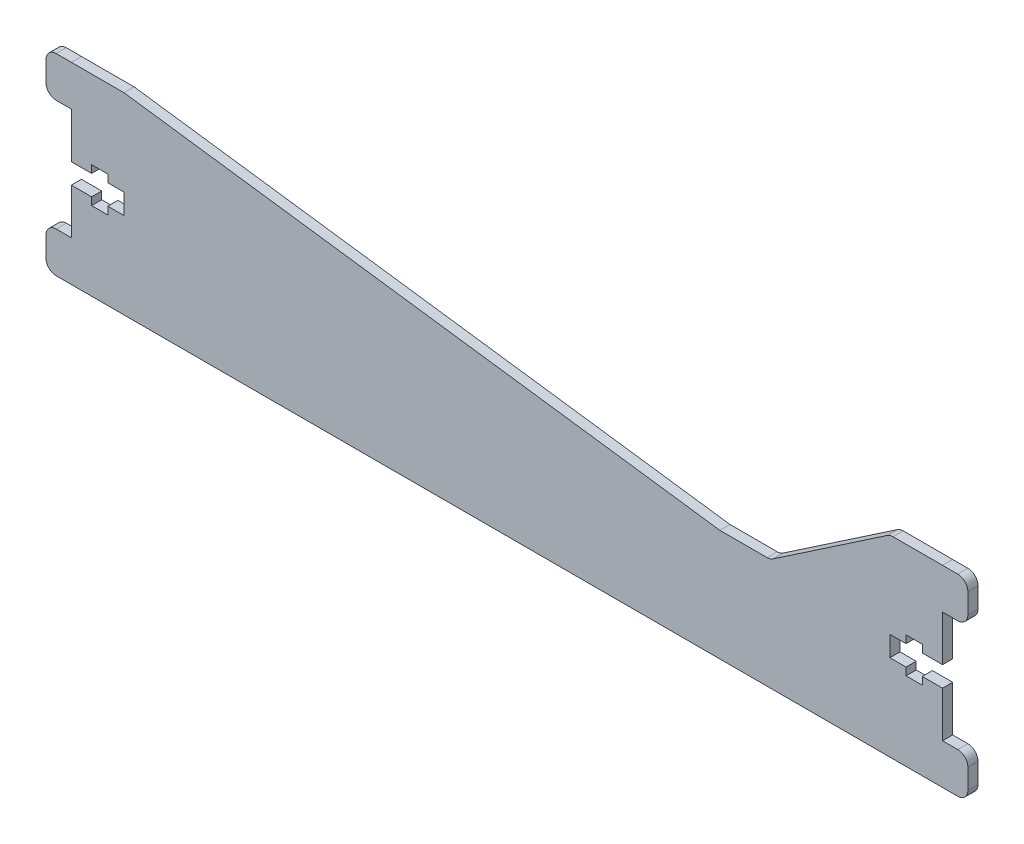
SolidWorks part; units mm, degrees
ref_plane "前视基准面" through (0, 0, 0) normal (0, 0, 1) x (1, 0, 0)
ref_plane "上视基准面" through (0, 0, 0) normal (0, 1, 0) x (1, 0, 0)
ref_plane "右视基准面" through (0, 0, 0) normal (1, 0, 0) x (0, 0, -1)
sketch "草图1" plane through (0, 0, 0) normal (0, 0, 1) x (1, 0, 0)
  line L0 (81.505, -9.4027) -> (76.5363, -9.4027) construction
  line L1 (81.505, 20.5973) -> (76.5363, 20.5973) construction
  line L2 (81.505, -5.4027) -> (76.505, -5.4027)
  line L3 (81.505, -13.4027) -> (81.505, -5.4027)
  line L4 (76.505, -13.4011) -> (81.505, -13.4027)
  line L5 (66.105, 5.5973) -> (77.8452, 5.5973) construction
  line L6 (76.505, 7.5973) -> (72.505, 7.5973)
  line L7 (72.505, 7.5973) -> (72.505, 9.0973)
  line L8 (72.505, 9.0973) -> (69.305, 9.0973)
  line L9 (69.305, 9.0973) -> (69.305, 7.5973)
  line L10 (69.305, 7.5973) -> (66.105, 7.5973)
  line L11 (69.305, 2.0973) -> (69.305, 3.5973)
  line L12 (72.505, 3.5973) -> (72.505, 2.0973)
  line L13 (69.305, 3.5973) -> (66.105, 3.5973)
  line L14 (72.505, 2.0973) -> (69.305, 2.0973)
  line L15 (76.505, 3.5973) -> (72.505, 3.5973)
  line L16 (76.505, 24.5956) -> (81.505, 24.5973)
  line L17 (81.505, 24.5973) -> (81.505, 16.5973)
  line L18 (81.505, 16.5973) -> (76.505, 16.5973)
  line L19 (76.505, 16.5973) -> (76.505, 7.5973)
  line L20 (76.505, -5.4027) -> (76.505, 3.5973)
  line L21 (76.505, 7.5973) -> (72.505, 7.5973)
  line L22 (72.505, 9.0973) -> (69.305, 9.0973)
  line L23 (76.505, 7.5973) -> (72.505, 7.5973)
  line L24 (72.505, 7.5973) -> (72.505, 9.0973)
  line L25 (72.505, 9.0973) -> (69.305, 9.0973)
  line L26 (69.305, 9.0973) -> (69.305, 7.5973)
  line L27 (69.305, 7.5973) -> (66.105, 7.5973)
  line L28 (69.305, 2.0973) -> (69.305, 3.5973)
  line L29 (72.505, 3.5973) -> (72.505, 2.0973)
  line L30 (69.305, 3.5973) -> (66.105, 3.5973)
  line L31 (72.505, 2.0973) -> (69.305, 2.0973)
  line L32 (76.505, 3.5973) -> (72.505, 3.5973)
  line L33 (69.305, 7.5973) -> (66.105, 7.5973)
  line L34 (72.505, 7.5973) -> (72.505, 9.0973)
  line L35 (69.305, 9.0973) -> (69.305, 7.5973)
  line L36 (69.305, 3.5973) -> (66.105, 3.5973)
  line L37 (69.305, 2.0973) -> (69.305, 3.5973)
  line L38 (72.505, 2.0973) -> (69.305, 2.0973)
  line L39 (72.505, 3.5973) -> (72.505, 2.0973)
  line L40 (76.505, 3.5973) -> (72.505, 3.5973)
  line L41 (42.505, 8.5956) -> (66.105, 24.5956)
  line L42 (53.0091, 24.5956) -> (53.0091, 9.0835) construction
  line L43 (-9.495, 24.1022) -> (-9.495, -22.6172) construction
  line L44 (-85.095, 5.5973) -> (-96.8351, 5.5973) construction
  line L45 (-100.495, 20.5973) -> (-95.5262, 20.5973) construction
  line L46 (-100.495, -9.4027) -> (-95.5262, -9.4027) construction
  line L47 (-95.495, 3.5973) -> (-91.495, 3.5973)
  line L48 (-91.495, 3.5973) -> (-91.495, 2.0973)
  line L49 (-91.495, 2.0973) -> (-88.295, 2.0973)
  line L50 (-88.295, 2.0973) -> (-88.295, 3.5973)
  line L51 (-88.295, 3.5973) -> (-85.095, 3.5973)
  line L52 (-85.095, 3.5973) -> (-85.095, 7.5973)
  line L53 (-88.295, 9.0973) -> (-88.295, 7.5973)
  line L54 (-91.495, 7.5973) -> (-91.495, 9.0973)
  line L55 (-88.295, 7.5973) -> (-85.095, 7.5973)
  line L56 (-91.495, 9.0973) -> (-88.295, 9.0973)
  line L57 (-95.495, 7.5973) -> (-91.495, 7.5973)
  line L58 (76.505, 7.5973) -> (72.505, 7.5973)
  line L59 (72.505, 9.0973) -> (69.305, 9.0973)
  line L60 (69.305, 7.5973) -> (66.105, 7.5973)
  line L61 (72.505, 7.5973) -> (72.505, 9.0973)
  line L62 (69.305, 9.0973) -> (69.305, 7.5973)
  line L63 (66.105, 3.5973) -> (66.105, 7.5973)
  line L64 (69.305, 3.5973) -> (66.105, 3.5973)
  line L65 (69.305, 2.0973) -> (69.305, 3.5973)
  line L66 (72.505, 2.0973) -> (69.305, 2.0973)
  line L67 (72.505, 3.5973) -> (72.505, 2.0973)
  line L68 (76.505, 3.5973) -> (72.505, 3.5973)
  line L69 (66.105, 24.5956) -> (76.505, 24.5956)
  line L70 (-95.495, 3.5973) -> (-91.495, 3.5973)
  line L71 (-91.495, 3.5973) -> (-91.495, 2.0973)
  line L72 (-91.495, 2.0973) -> (-88.295, 2.0973)
  line L73 (-88.295, 2.0973) -> (-88.295, 3.5973)
  line L74 (-88.295, 3.5973) -> (-85.095, 3.5973)
  line L76 (-88.295, 9.0973) -> (-88.295, 7.5973)
  line L78 (-91.495, 7.5973) -> (-91.495, 9.0973)
  line L79 (-88.295, 7.5973) -> (-85.095, 7.5973)
  line L81 (-95.495, 3.5973) -> (-91.495, 3.5973)
  line L82 (-91.495, 2.0973) -> (-88.295, 2.0973)
  line L83 (-88.295, 3.5973) -> (-85.095, 3.5973)
  line L84 (-91.495, 3.5973) -> (-91.495, 2.0973)
  line L85 (-88.295, 2.0973) -> (-88.295, 3.5973)
  line L86 (-88.295, 7.5973) -> (-85.095, 7.5973)
  line L87 (-88.295, 9.0973) -> (-88.295, 7.5973)
  line L88 (-91.495, 9.0973) -> (-88.295, 9.0973)
  line L89 (-91.495, 7.5973) -> (-91.495, 9.0973)
  line L90 (-95.495, 7.5973) -> (-91.495, 7.5973)
  line L92 (-91.495, 9.0973) -> (-88.295, 9.0973)
  line L94 (-95.495, 7.5973) -> (-91.495, 7.5973)
  line L95 (-95.495, -5.4027) -> (-95.495, 3.5973)
  line L97 (-95.495, 16.5973) -> (-95.495, 7.5973)
  line L98 (-100.495, 16.5973) -> (-95.495, 16.5973)
  line L99 (-100.495, 24.5973) -> (-100.495, 16.5973)
  line L100 (-95.495, 24.5956) -> (-100.495, 24.5973)
  line L101 (-95.495, 3.5973) -> (-91.495, 3.5973)
  line L102 (-91.495, 2.0973) -> (-88.295, 2.0973)
  line L103 (-88.295, 3.5973) -> (-85.095, 3.5973)
  line L104 (-91.495, 3.5973) -> (-91.495, 2.0973)
  line L105 (-88.295, 2.0973) -> (-88.295, 3.5973)
  line L106 (-88.295, 7.5973) -> (-85.095, 7.5973)
  line L107 (-88.295, 9.0973) -> (-88.295, 7.5973)
  line L108 (-91.495, 9.0973) -> (-88.295, 9.0973)
  line L109 (-91.495, 7.5973) -> (-91.495, 9.0973)
  line L110 (-95.495, 7.5973) -> (-91.495, 7.5973)
  line L111 (-95.495, -13.4011) -> (-100.495, -13.4027)
  line L112 (-100.495, -13.4027) -> (-100.495, -5.4027)
  line L113 (-100.495, -5.4027) -> (-95.495, -5.4027)
  line L114 (-95.495, -13.4011) -> (76.505, -13.4011)
  line L115 (42.505, 8.5956) -> (32.5358, 8.5956)
  line L116 (32.5358, 8.5956) -> (-85.095, 24.5956)
  line L117 (-85.095, 24.5956) -> (-95.495, 24.5956)
  dimension "D1" = 172
  dimension "D2" = 7
  dimension "D3" = 4
  dimension "D4" = 8
  dimension "D5" = 4
  dimension "D6" = 3.2
  dimension "D7" = 5
  dimension "D8" = 15
extrude "凸台-拉伸1" add sketch "草图1" along normal blind 2
sketch "草图2" plane through (76.505, 0, 0) normal (1, 0, 0) x (0, 0, -1)
  line L0 (-1, 3.5973) -> (-1, 7.5973)
  line L1 (-2, 3.5973) -> (0, 3.5973) construction
  line L2 (-2, 7.5973) -> (0, 7.5973) construction
  circle A0 centre (-1, 5.5973) radius 2
fillet "圆角1" radius 2 10 edges at (81.505, -5.4027, 1) (81.505, 16.5973, 1) (-100.495, -5.4027, 1) (-100.495, 16.5973, 1) (-100.495, -13.4027, 1) (-100.495, 24.5973, 1) (81.505, 24.5973, 1) (81.505, -13.4027, 1) (42.505, 8.5956, 1) (66.105, 24.5956, 1)
